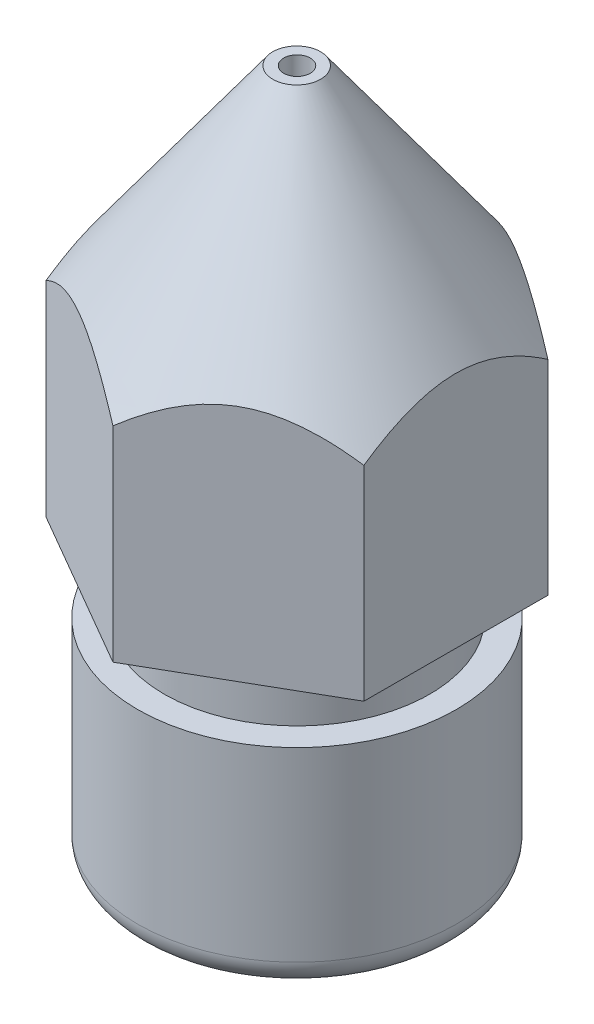
SolidWorks part; units mm, degrees
material "Copper"
ref_plane "Front Plane" through (0, 0, 0) normal (0, 0, 1) x (1, 0, 0)
ref_plane "Top Plane" through (0, 0, 0) normal (0, 1, 0) x (1, 0, 0)
ref_plane "Right Plane" through (0, 0, 0) normal (1, 0, 0) x (0, 0, -1)
sketch "Sketch1" plane through (0, 0, 0) normal (0, 1, 0) x (1, 0, 0)
  line L1 (-2.9993, -1.7251) -> (-0.0057, -3.46)
  line L2 (-0.0057, -3.46) -> (2.9936, -1.7349)
  line L3 (2.9936, -1.7349) -> (2.9993, 1.7251)
  line L4 (2.9993, 1.7251) -> (0.0057, 3.46)
  line L5 (0.0057, 3.46) -> (-2.9936, 1.7349)
  line L6 (-2.9936, 1.7349) -> (-2.9993, -1.7251)
  circle A0 centre (0, 0) radius 2.9964 construction
  dimension "D1" = 3.46
extrude "Boss-Extrude1" add sketch "Sketch1" along normal blind 8
sketch "Sketch2" plane through (0, 0, 0) normal (0, 0, 1) x (1, 0, 0)
  line L0 (-0.0057, 8) -> (-0.0057, 3.7644) construction
  line L1 (-0.0057, 8) -> (-0.0057, 0) construction
  line L8 (-0.4557, 8) -> (-4.1943, 2.85)
  line L9 (-2.9993, 8) -> (-0.0057, 8) construction
  line L10 (-4.1943, 2.85) -> (-4.1943, 8)
  line L11 (-0.4557, 8) -> (-4.1943, 8)
  dimension "D1" = 0.45
  dimension "D2" = 6.3639
  dimension "D3" = 5.15
revolve "Cut-Revolve2" cut sketch "Sketch2" angle 360 about L0
sketch "Sketch3" plane through (0, 0, 0) normal (0, -1, 0) x (1, 0, 0)
  circle A0 centre (0, 0) radius 2.5
  dimension "D1" = 5
extrude "Boss-Extrude2" add sketch "Sketch3" along normal blind 1
sketch "Sketch4" plane through (0, -1, 0) normal (0, -1, 0) x (1, 0, 0)
  circle A0 centre (0, 0) radius 3
  dimension "D1" = 6
extrude "Boss-Extrude3" add sketch "Sketch4" along normal blind 4
fillet "Fillet1" radius 0.5 1 edges at (0, -5, -3)
sketch "Sketch5" plane through (0, 8, 0) normal (0, 1, 0) x (1, 0, 0)
  circle A0 centre (0, 0) radius 0.25
  dimension "D1" = 0.5
extrude "Cut-Extrude1" cut sketch "Sketch5" against normal blind 100
chamfer "Chamfer1" distance 1 angle 77 1 edges at (0, -5, -0.25)
chamfer "Chamfer2" distance 0.25 angle 45 1 edges at (0, -5, -1.25)
